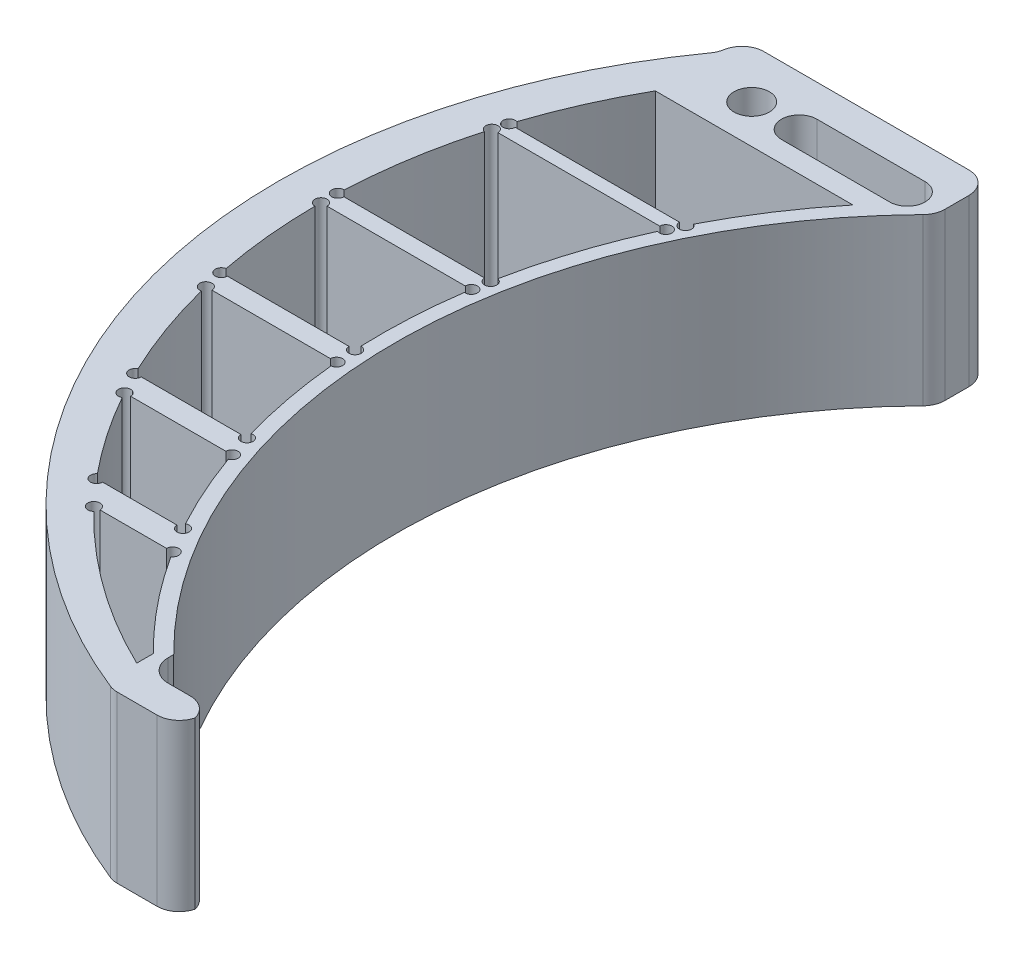
SolidWorks part; units mm, degrees
ref_plane "Plan de face" through (0, 0, 0) normal (0, 0, 1) x (1, 0, 0)
ref_plane "Plan de dessus" through (0, 0, 0) normal (0, 1, 0) x (1, 0, 0)
ref_plane "Plan de droite" through (0, 0, 0) normal (1, 0, 0) x (0, 0, -1)
sketch "Esquisse1" plane through (0, 0, 0) normal (0, 1, 0) x (1, 0, 0)
  line L0 (0.3799, -77.5) -> (4, -77.5)
  line L1 (4, -74.5) -> (2, -74.5)
  line L2 (0, -72.5) -> (0, -72)
  line L3 (0, -2.1735) -> (0, 0)
  line L4 (-2, 2) -> (-20.553, 2)
  line L5 (-26.2459, -16.4) -> (-11.5931, -16.4)
  line L6 (-15.4482, -28.4) -> (-28.1858, -28.4)
  line L7 (-28.2169, -29.9) -> (-15.7035, -29.9)
  line L8 (-16.2293, -39.9) -> (-27.2418, -39.9)
  line L9 (-14.2184, -51.7) -> (-23.2365, -51.7)
  line L10 (-26.8418, -41.7) -> (-16.1097, -41.7)
  line L11 (-22.2015, -53.7) -> (-13.5768, -53.7)
  line L12 (-10.0074, -61.7) -> (-16.7342, -61.7)
  line L13 (-14.6761, -64) -> (-8.6454, -64)
  line L14 (-1, -72.8514) -> (-1, -74.3514)
  line L15 (-3.0684, -4.1) -> (-12.8684, -4.1)
  line L16 (-12.8684, -0.9) -> (-3.0684, -0.9)
  line L17 (-11.0116, -15.2) -> (-25.8782, -15.2)
  line L18 (-22.4, -6) -> (-4.5, -6)
  arc A0 (4, -77.5) -> (5.9365, -76) centre (4, -75.5) ccw
  arc A1 (5.9365, -76) -> (4, -74.5) centre (4, -76.5) ccw
  arc A2 (2, -74.5) -> (0, -72.5) centre (2, -72.5) cw
  arc A3 (0, -72) -> (-0.5719, -3.5736) centre (34.0316, -37.5) cw
  arc A4 (-0.5719, -3.5736) -> (0, -2.1735) centre (-2, -2.1735) ccw
  arc A5 (0, 0) -> (-2, 2) centre (-2, 0) ccw
  arc A6 (-20.553, 2) -> (-22.5265, 0.3246) centre (-20.553, 0) ccw
  arc A7 (-22.5265, 0.3246) -> (-22.874, -0.5154) centre (-24.5, 0.6492) cw
  arc A8 (-22.874, -0.5154) -> (-0.3606, -77.3579) centre (18.4642, -30.1233) ccw
  arc A9 (-0.3606, -77.3579) -> (0.3799, -77.5) centre (0.3799, -75.5) ccw
  arc A10 (-11.5931, -16.4) -> (-11.2735, -16.8994) centre (-11.0431, -16.4) cw
  arc A11 (-11.2735, -16.8994) -> (-14.7946, -27.8598) centre (34.0316, -37.5) ccw
  arc A12 (-14.7946, -27.8598) -> (-15.4482, -28.4) centre (-14.8982, -28.4) cw
  arc A13 (-28.1858, -28.4) -> (-28.7129, -27.8505) centre (-28.7358, -28.4) cw
  arc A14 (-28.7129, -27.8505) -> (-26.9473, -16.9287) centre (20.2718, -30.1657) cw
  arc A15 (-26.9473, -16.9287) -> (-26.2459, -16.4) centre (-26.7959, -16.4) cw
  arc A16 (-27.8979, -39.3603) -> (-28.7668, -30.45) centre (20.2718, -30.1657) cw
  arc A17 (-28.7668, -30.45) -> (-28.2169, -29.9) centre (-28.7669, -29.9) cw
  arc A18 (-15.7035, -29.9) -> (-15.2345, -30.444) centre (-15.1535, -29.9) cw
  arc A19 (-15.2345, -30.444) -> (-15.7028, -39.3505) centre (34.0316, -37.5) ccw
  arc A20 (-15.7028, -39.3505) -> (-16.2293, -39.9) centre (-15.6793, -39.9) cw
  arc A21 (-27.2418, -39.9) -> (-27.8979, -39.3603) centre (-27.7918, -39.9) cw
  arc A22 (-23.2365, -51.7) -> (-24.0253, -51.2045) centre (-23.7865, -51.7) cw
  arc A23 (-24.0253, -51.2045) -> (-27.2595, -42.2338) centre (20.2718, -30.1657) cw
  arc A24 (-27.2595, -42.2338) -> (-26.8418, -41.7) centre (-27.3918, -41.7) cw
  arc A25 (-16.1097, -41.7) -> (-15.5102, -42.2478) centre (-15.5597, -41.7) cw
  arc A26 (-15.5102, -42.2478) -> (-13.8225, -51.172) centre (34.0316, -37.5) ccw
  arc A27 (-13.8225, -51.172) -> (-14.2184, -51.7) centre (-13.6684, -51.7) cw
  arc A28 (-13.5768, -53.7) -> (-12.8449, -54.219) centre (-13.0268, -53.7) cw
  arc A29 (-12.8449, -54.219) -> (-9.7222, -61.2179) centre (34.0316, -37.5) ccw
  arc A30 (-9.7222, -61.2179) -> (-10.0074, -61.7) centre (-9.4574, -61.7) cw
  arc A31 (-16.7342, -61.7) -> (-17.6355, -61.2768) centre (-17.2842, -61.7) cw
  arc A32 (-17.6355, -61.2768) -> (-22.4848, -54.181) centre (20.2718, -30.1657) cw
  arc A33 (-22.4848, -54.181) -> (-22.2015, -53.7) centre (-22.7515, -53.7) cw
  arc A34 (-8.6454, -64) -> (-7.8, -64.4639) centre (-8.0954, -64) cw
  arc A35 (-7.8, -64.4639) -> (-1, -72.8514) centre (34.0316, -37.5) ccw
  arc A36 (-1, -74.3514) -> (-14.8445, -64.396) centre (20.2718, -30.1657) cw
  arc A37 (-14.8445, -64.396) -> (-14.6761, -64) centre (-15.2261, -64) cw
  arc A38 (-3.0684, -0.9) -> (-3.0684, -4.1) centre (-3.0684, -2.5) cw
  arc A39 (-12.8684, -4.1) -> (-12.8684, -0.9) centre (-12.8684, -2.5) cw
  circle A40 centre (-17.1685, -2.5) radius 1.6
  arc A41 (-25.8782, -15.2) -> (-26.2574, -14.6772) centre (-26.4282, -15.2) cw
  arc A42 (-26.2574, -14.6772) -> (-22.4, -6) centre (20.2718, -30.1657) cw
  arc A43 (-4.5, -6) -> (-10.2124, -14.7097) centre (34.0316, -37.5) ccw
  arc A44 (-10.2124, -14.7097) -> (-11.0116, -15.2) centre (-10.4616, -15.2) cw
extrude "Boss.-Extru.1" add sketch "Esquisse1" against normal blind 15
